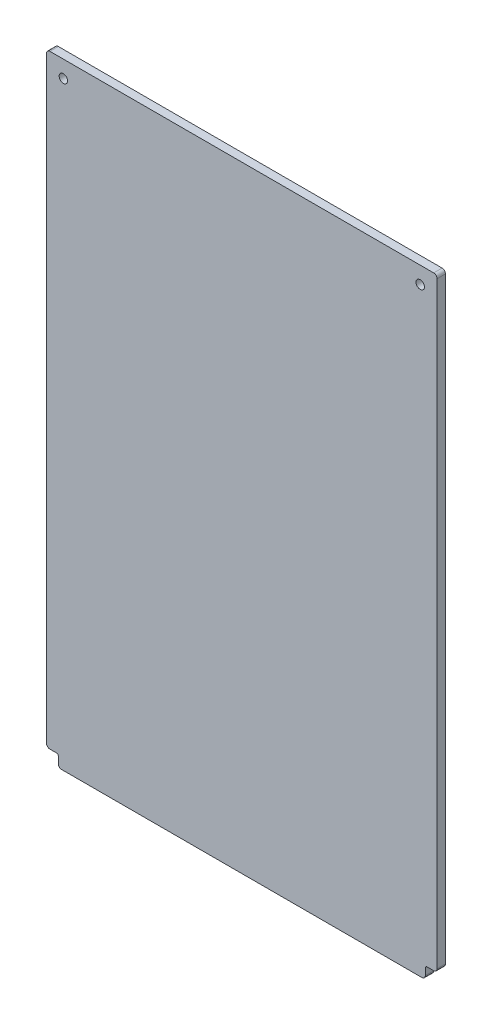
SolidWorks part; units mm, degrees
ref_plane "Front Plane" through (0, 0, 0) normal (0, 0, 1) x (1, 0, 0)
ref_plane "Top Plane" through (0, 0, 0) normal (0, 1, 0) x (1, 0, 0)
ref_plane "Right Plane" through (0, 0, 0) normal (1, 0, 0) x (0, 0, -1)
sketch "Sketch1" plane through (0, 0, 0) normal (0, 0, 1) x (1, 0, 0)
  line L0 (0, 0) -> (294.64, 0) construction
  line L1 (0, 0) -> (0, 464.82) construction
  line L2 (294.64, 0) -> (294.64, 464.82) construction
  line L3 (0, 464.82) -> (294.64, 464.82)
  line L4 (0, 8.89) -> (8.89, 8.89)
  line L5 (8.89, 8.89) -> (8.89, 0)
  line L6 (8.89, 0) -> (285.75, 0)
  line L7 (285.75, 0) -> (285.75, 8.89)
  line L8 (285.75, 8.89) -> (294.64, 8.89)
  line L9 (294.64, 8.89) -> (294.64, 464.82)
  line L10 (0, 464.82) -> (0, 8.89)
  circle A0 centre (12.7, 452.12) radius 3.175
  circle A1 centre (281.94, 452.12) radius 3.175
  point P15 (0, 0)
  point P18 (0, 456.8937)
  dimension "D7" = 6.35
  dimension "D1" = 464.82
  dimension "D2" = 294.64
  dimension "D3" = 8.89
  dimension "D4" = 12.7
  dimension "D5" = 12.7
  dimension "D6" = 12.7
extrude "Boss-Extrude1" add sketch "Sketch1" along normal blind 6.35
fillet "Fillet1" radius 1.27 2 edges at (8.89, 8.89, 3.175) (285.75, 8.89, 3.175)
fillet "Fillet2" radius 2.54 6 edges at (0, 8.89, 3.175) (8.89, 0, 3.175) (285.75, 0, 3.175) (294.64, 8.89, 3.175) (294.64, 464.82, 3.175) (0, 464.82, 3.175)
